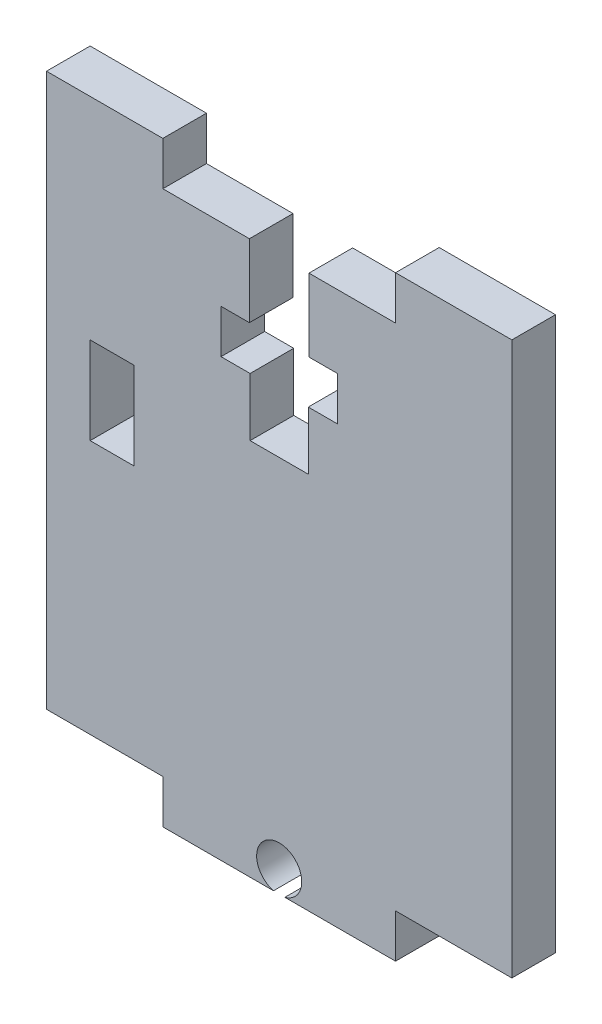
SolidWorks part; units mm, degrees
ref_plane "前视" through (0, 0, 0) normal (0, 0, 1) x (1, 0, 0)
ref_plane "上视" through (0, 0, 0) normal (0, 1, 0) x (1, 0, 0)
ref_plane "右视" through (0, 0, 0) normal (1, 0, 0) x (0, 0, -1)
sketch "草图2" plane through (0, 0, 0) normal (0, 0, 1) x (1, 0, 0)
  line L0 (0, 103.0974) -> (0, -63.3868) construction
  line L1 (2.0479, 48.8553) -> (8, 48.8553)
  line L2 (8, 48.8553) -> (8, 51.8553)
  line L3 (8, 51.8553) -> (16, 51.8553)
  line L4 (16, 51.8553) -> (16, 13.8553)
  line L5 (16, 13.8553) -> (8, 13.8553)
  line L6 (2.0479, 48.8553) -> (2.0479, 43.8553)
  line L7 (2.0479, 43.8553) -> (4, 43.8553)
  line L8 (4, 43.8553) -> (4, 40.8553)
  line L9 (4, 40.8553) -> (2, 40.8553)
  line L10 (2, 40.8553) -> (2, 36.8553)
  line L11 (2, 36.8553) -> (-2, 36.8553)
  line L12 (-8, 10.8553) -> (-0.3905, 10.8553)
  line L13 (8, 10.8553) -> (8, 13.8553)
  line L14 (-8, 10.8553) -> (-8, 13.8553)
  line L15 (0.3905, 10.8553) -> (8, 10.8553)
  line L16 (-2, 40.8553) -> (-2, 36.8553)
  line L17 (-4, 40.8553) -> (-2, 40.8553)
  line L18 (-4, 43.8553) -> (-4, 40.8553)
  line L19 (-2.0479, 43.8553) -> (-4, 43.8553)
  line L20 (-2.0479, 48.8553) -> (-2.0479, 43.8553)
  line L21 (-16, 13.8553) -> (-8, 13.8553)
  line L22 (-16, 51.8553) -> (-16, 13.8553)
  line L23 (-8, 51.8553) -> (-16, 51.8553)
  line L24 (-8, 48.8553) -> (-8, 51.8553)
  line L25 (-2.0479, 48.8553) -> (-8, 48.8553)
  line L27 (-13, 31.3553) -> (-10, 31.3553)
  line L28 (-13, 31.3553) -> (-13, 37.3553)
  line L29 (-13, 37.3553) -> (-10, 37.3553)
  line L30 (-10, 31.3553) -> (-10, 37.3553)
  arc A0 (0.3905, 10.8553) -> (-0.3905, 10.8553) centre (0, 12.3553) ccw
  point P22 (0, 36.8553)
  dimension "D12" = 1.5
  dimension "D11" = 3.1
  dimension "D1" = 8
  dimension "D2" = 8
  dimension "D3" = 3
  dimension "D4" = 12
  dimension "D5" = 5
  dimension "D6" = 3
  dimension "D7" = 2
  dimension "D8" = 2
  dimension "D9" = 35
  dimension "D10" = 3
  dimension "D13" = 3
  dimension "D14" = 6
  dimension "D15" = 3
  dimension "D16" = 11.5
extrude "凸台-拉伸1" add sketch "草图2" along normal blind 3
